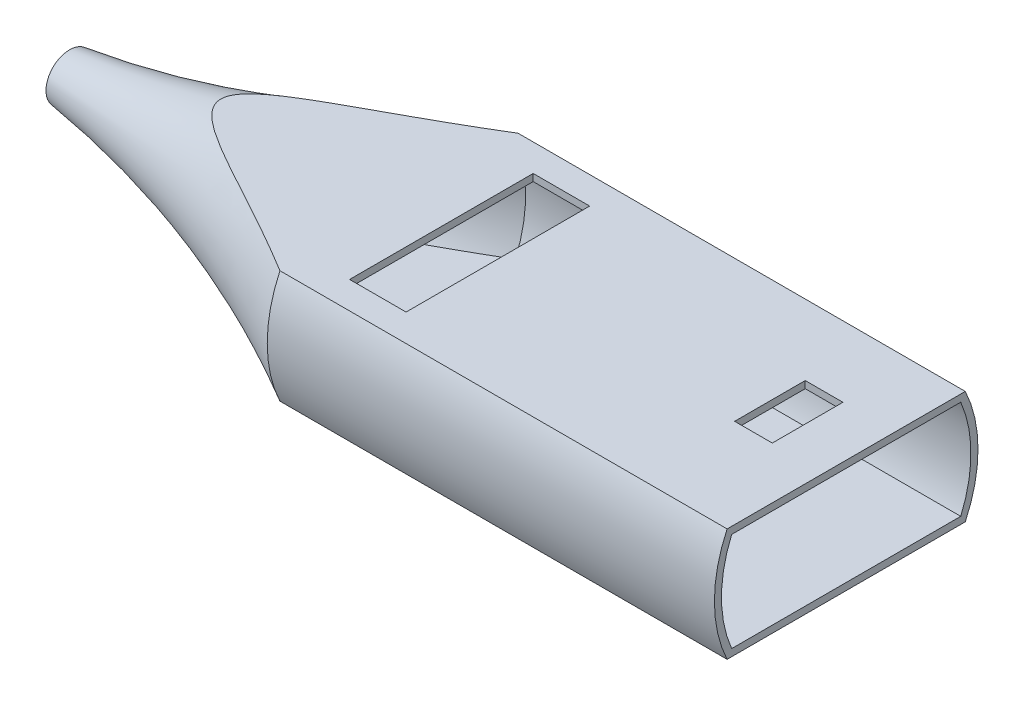
SolidWorks part; units mm, degrees
ref_plane "Plano frontal" through (0, 0, 0) normal (0, 0, 1) x (1, 0, 0)
ref_plane "Plano superior" through (0, 0, 0) normal (0, 1, 0) x (1, 0, 0)
ref_plane "Plano direito" through (0, 0, 0) normal (1, 0, 0) x (0, 0, -1)
sketch "Esboço7" plane through (0, 0, 0) normal (0, 0, 1) x (1, 0, 0)
  line L0 (-70.455, 0) -> (124.6572, 0) construction
  line L1 (-58.6729, 0) -> (-58.6729, 5)
  line L4 (11.3271, 28) -> (106.3271, 28)
  line L5 (106.3271, 28) -> (106.3271, 0)
  line L6 (-58.6729, 0) -> (106.3271, 0) construction
  line L7 (-58.6729, 0) -> (106.3271, 0)
  arc A1 (11.3271, 28) -> (-58.6729, 5) centre (-85.0353, 203.255) cw
  dimension "D4" = 200
  dimension "D1" = 5
  dimension "D2" = 95
  dimension "D3" = 28
  dimension "D5" = 106.3271
revolve "Revolução1" add sketch "Esboço7" angle 360 about L0
sketch "Esboço8" plane through (106.3271, 0, 0) normal (1, 0, 0) x (0, 0, -1)
  line L0 (-25.2982, 12) -> (25.2982, 12)
  line L1 (-25.2982, -12) -> (25.2982, -12)
  circle A0 centre (0, 0) radius 28 construction
  arc A2 (25.2982, 12) -> (-25.2982, 12) centre (0, 0) ccw
  circle A3 centre (0, 0) radius 28
  arc A4 (-25.2982, -12) -> (25.2982, -12) centre (0, 0) ccw
  point P9 (9.2942, -3.6957)
  dimension "D1" = 12
  dimension "D2" = 12
  dimension "D3" = 0
extrude "Corte-extrusão2" cut sketch "Esboço8" against normal through all
shell "Casca2" thickness 1.5
sketch "Esboço9" plane through (-58.6729, 0, 0) normal (-1, 0, 0) x (0, 0, 1)
  circle A0 centre (0, 0) radius 3
  dimension "D1" = 6
extrude "Corte-extrusão3" cut sketch "Esboço9" against normal through all
sketch "Esboço10" plane through (0, 12, 0) normal (0, 1, 0) x (1, 0, 0)
  line L0 (20.3271, 19.5) -> (32.3271, 19.5)
  line L1 (32.3271, 19.5) -> (32.3271, -19.5)
  line L2 (32.3271, -19.5) -> (20.3271, -19.5)
  line L3 (20.3271, -19.5) -> (20.3271, 19.5)
  line L4 (106.3271, -25.2982) -> (106.3271, 25.2982) construction
  line L7 (11.3271, -28) -> (106.3271, -28) construction
  dimension "D1" = 74
  dimension "D2" = 39
  dimension "D3" = 8.5
  dimension "D4" = 12
extrude "Corte-extrusão4" cut sketch "Esboço10" against normal up to surface (1.5 mm away) up to face at (49.5305, 10.5, 0.1722)
sketch "Esboço11" plane through (0, 12, 0) normal (0, 1, 0) x (1, 0, 0)
  line L0 (87.3271, 10.2982) -> (95.3271, 10.2982)
  line L1 (95.3271, 10.2982) -> (95.3271, -4.7018)
  line L2 (95.3271, -4.7018) -> (87.3271, -4.7018)
  line L3 (87.3271, -4.7018) -> (87.3271, 10.2982)
  line L4 (106.3271, -25.2982) -> (106.3271, 25.2982) construction
  line L6 (11.3271, 25.2982) -> (106.3271, 25.2982) construction
  dimension "D1" = 19
  dimension "D2" = 8
  dimension "D3" = 15
  dimension "D4" = 30
extrude "Corte-extrusão5" cut sketch "Esboço11" against normal up to surface (1.5 mm away) up to face at (26.3271, 10.5, 0)
